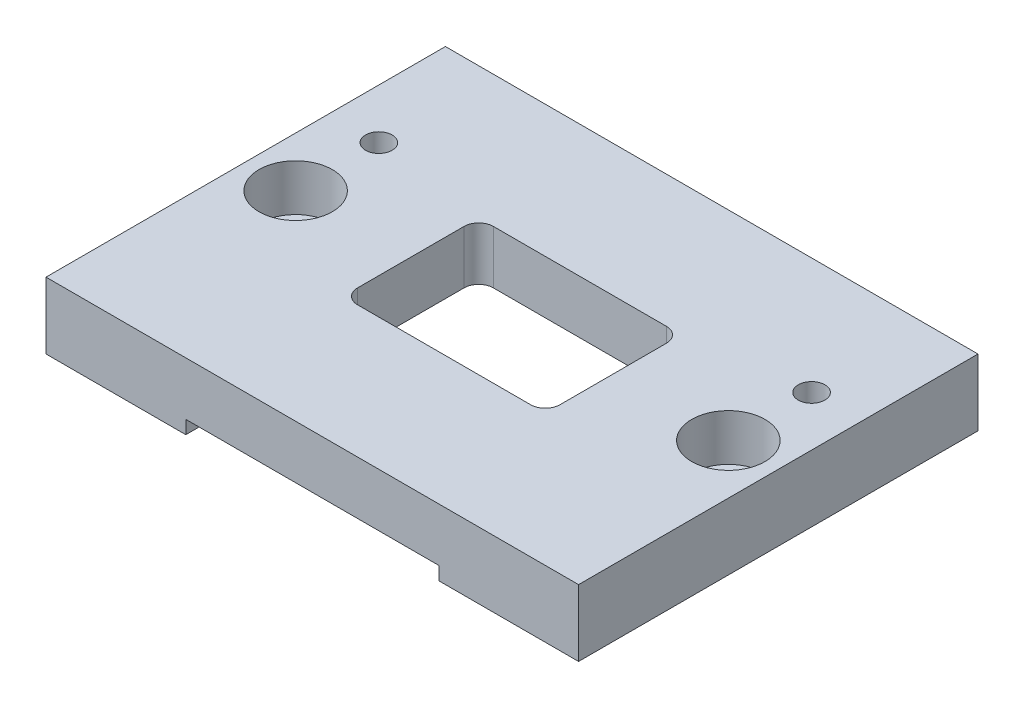
SolidWorks part; units mm, degrees
ref_plane "Front Plane" through (0, 0, 0) normal (0, 0, 1) x (1, 0, 0)
ref_plane "Top Plane" through (0, 0, 0) normal (0, 1, 0) x (1, 0, 0)
ref_plane "Right Plane" through (0, 0, 0) normal (1, 0, 0) x (0, 0, -1)
sketch "Sketch1" plane through (0, 0, 0) normal (0, 1, 0) x (1, 0, 0)
  line L0 (-70.0403, 36.463) -> (9.9597, 36.463)
  line L1 (9.9597, 36.463) -> (9.9597, -23.537)
  line L2 (9.9597, -23.537) -> (-70.0403, -23.537)
  line L3 (-70.0403, -23.537) -> (-70.0403, 36.463)
  line L4 (-70.0403, -23.537) -> (-70.0403, 6.463) construction
  line L7 (-70.0403, -23.537) -> (-70.0403, 18.963) construction
  line L9 (-70.0403, -23.537) -> (-70.0403, -3.737) construction
  line L11 (-70.0403, -23.537) -> (-70.0403, 16.663) construction
  point P28 (0, 0)
extrude "Boss-Extrude3" add sketch "Sketch1" against normal blind 10 contours L0 L1 L2 L3
sketch "Sketch2" plane through (0, 0, 0) normal (0, 1, 0) x (1, 0, 0)
  circle A0 centre (-62.5403, 6.463) radius 5.5
  circle A1 centre (2.4597, 6.463) radius 5.5
extrude "Cut-Extrude2" cut sketch "Sketch2" against normal blind 7
sketch "Sketch3" plane through (0, 0, 0) normal (0, 1, 0) x (1, 0, 0)
  circle A0 centre (-62.5403, 18.963) radius 2
  circle A2 centre (2.4597, 18.963) radius 2
extrude "Cut-Extrude3" cut sketch "Sketch3" against normal blind 10
sketch "Sketch4" plane through (0, 0, 0) normal (0, 1, 0) x (1, 0, 0)
  line L8 (-43.0403, 16.663) -> (-17.0403, 16.663)
  line L9 (-14.8403, 14.463) -> (-14.8403, -1.537)
  line L10 (-17.0403, -3.737) -> (-43.0403, -3.737)
  line L11 (-45.2403, -1.537) -> (-45.2403, 14.463)
  arc A0 (-43.0403, -3.737) -> (-45.2403, -1.537) centre (-43.0403, -1.537) cw
  arc A1 (-14.8403, -1.537) -> (-17.0403, -3.737) centre (-17.0403, -1.537) cw
  arc A2 (-17.0403, 16.663) -> (-14.8403, 14.463) centre (-17.0403, 14.463) cw
  arc A3 (-45.2403, 14.463) -> (-43.0403, 16.663) centre (-43.0403, 14.463) cw
  dimension "D1" = 2.2
extrude "Cut-Extrude4" cut sketch "Sketch4" against normal blind 8
ref_plane "Plane1" through (0, 0, 23.537) normal (0, 0, 1) x (1, 0, 0)
sketch "Sketch6" plane through (0, 0, 23.537) normal (0, 0, 1) x (1, 0, 0)
  line L0 (-49.0403, -10) -> (-49.0403, -8)
  line L2 (9.9597, -10) -> (-70.0403, -10) construction
  line L3 (-49.0403, -8) -> (-11.0403, -8)
  line L4 (-49.0403, -10) -> (-11.0403, -10)
  line L5 (-11.0403, -8) -> (-11.0403, -10)
extrude "Cut-Extrude5" cut sketch "Sketch6" against normal blind 60
sketch "Sketch7" plane through (0, 0, 0) normal (0, 1, 0) x (1, 0, 0)
  circle A0 centre (-62.5403, 6.463) radius 3.3
  circle A1 centre (2.4597, 6.463) radius 3.3
extrude "Cut-Extrude7" cut sketch "Sketch7" against normal blind 13
